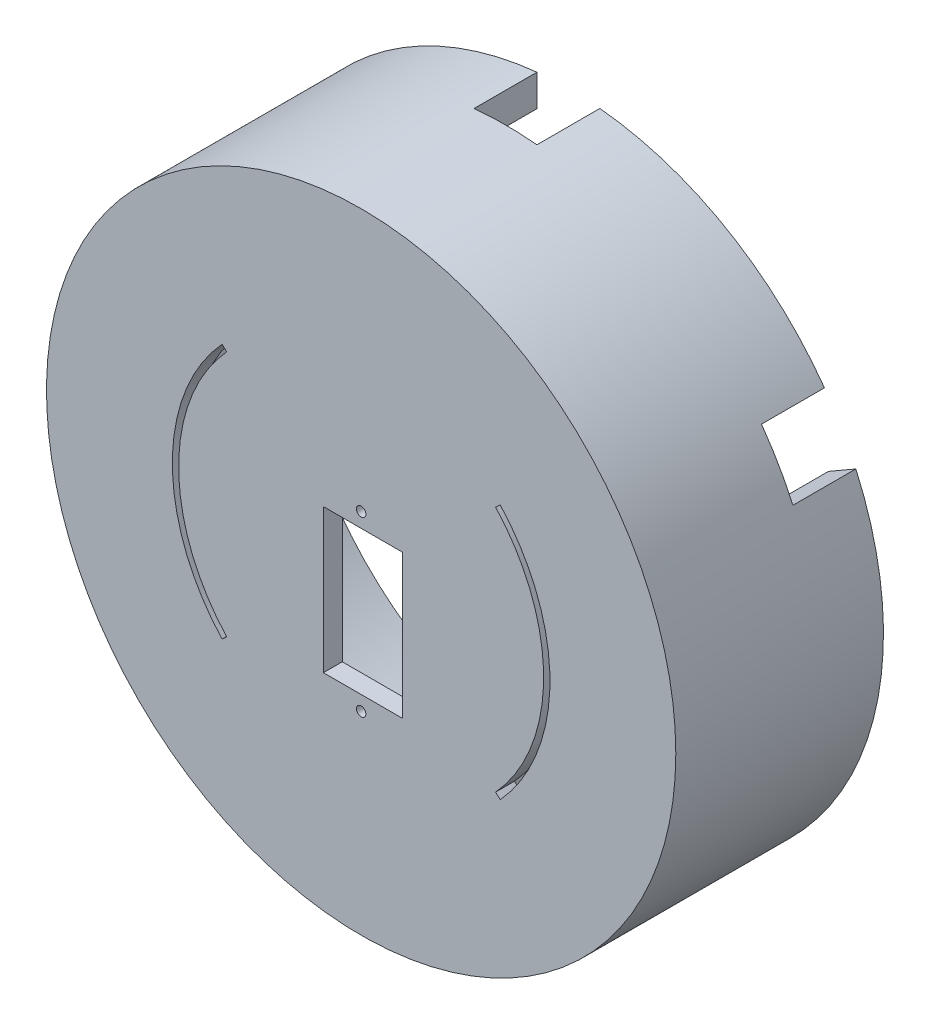
SolidWorks part; units mm, degrees
ref_plane "Front Plane" through (0, 0, 0) normal (0, 0, 1) x (1, 0, 0)
ref_plane "Top Plane" through (0, 0, 0) normal (0, 1, 0) x (1, 0, 0)
ref_plane "Right Plane" through (0, 0, 0) normal (1, 0, 0) x (0, 0, -1)
sketch "Sketch1" plane through (0, 0, 0) normal (0, 0, 1) x (1, 0, 0)
  line L0 (-5.1956, 27.9914) -> (49994.8044, 27.9914) construction
  line L1 (-6, -2.32) -> (6.6, -2.32) construction
  line L2 (-5.002, -4.6686) -> (49994.998, -4.6686) construction
  line L3 (-5.7, 27.9914) -> (6.9, 27.9914)
  line L4 (6.9, 10.7264) -> (6.9, 50010.7264) construction
  line L5 (-6, 16.86) -> (6.6, 16.86) construction
  line L6 (-5.7, 12.1783) -> (-5.7, 50012.1783) construction
  line L7 (-5.7, 22.86) -> (6.9, 22.86)
  line L8 (-5.7, 0) -> (6.9, 0)
  line L11 (-5.7, -4.6686) -> (6.9, -4.6686)
  line L13 (0.6, -4.6686) -> (0.6, 28.06) construction
  line L16 (-6, 25.18) -> (6.6, 25.18) construction
  line L19 (0.6, 28.06) -> (0.6, 22.86) construction
  line L20 (-5.7, 27.9914) -> (-5.7, 22.86)
  line L21 (-5.7, 0) -> (6.9, 0)
  line L22 (-5.7, 0) -> (-5.7, -4.6686)
  line L23 (-5.7, -4.6686) -> (6.9, -4.6686)
  line L24 (6.9, 0) -> (6.9, -4.6686)
  line L25 (0.6, -4.6686) -> (0.6, 0) construction
  line L26 (-5.7, -2.3343) -> (6.9, -2.3343) construction
  line L27 (6.9, 27.9914) -> (6.9, 22.86)
  line L29 (-5.7, 22.86) -> (6.9, 22.86)
  line L30 (-5.7, 22.86) -> (-5.7, 0)
  line L31 (-5.7, 0) -> (6.9, 0)
  line L32 (6.9, 22.86) -> (6.9, 0)
  line L33 (0.6, 0) -> (0.6, 22.86) construction
  line L34 (-5.7, 11.43) -> (6.9, 11.43) construction
  circle A3 centre (0.3, 25.18) radius 1.28
  circle A4 centre (0.3, -2.32) radius 1.28
  circle A5 centre (0.3, 16.86) radius 50
  point P287 (0.6, -2.3343)
  point P359 (0.6, 25.46)
  point P550 (0.6, 11.73)
  point P577 (0.6, 11.43)
  dimension "D3" = 100
  dimension "D4" = 2.56
  dimension "D5" = 2.56
  dimension "D1" = 12.6
  dimension "D2" = 32.66
extrude "Boss-Extrude2" add sketch "Sketch1" along normal blind 3 contours A5
sketch "Sketch2" plane through (0, 0, 0) normal (0, 0, -1) x (-1, 0, 0)
  line L1 (5.7, 0) -> (-6.9, 0)
  line L2 (5.7, 0) -> (5.7, 22.86)
  line L3 (5.7, 22.86) -> (-6.9, 22.86)
  line L4 (-6.9, 0) -> (-6.9, 22.86)
  line L5 (-0.6, 22.86) -> (-0.6, 0) construction
  line L6 (5.7, 11.43) -> (-6.9, 11.43) construction
  circle A0 centre (-0.3, -2.32) radius 0.75
  circle A1 centre (-0.3, 25.18) radius 0.75
  point P364 (-0.6, 11.43)
  dimension "D1" = 1.5
  dimension "D2" = 1.5
sketch "Sketch4" plane through (0, 0, 0) normal (0, 0, -1) x (-1, 0, 0)
  circle A0 centre (-0.3, 16.86) radius 50
  circle A1 centre (-0.3, 16.86) radius 45
  dimension "D1" = 5
  dimension "D2" = 100
extrude "Boss-Extrude3" add sketch "Sketch4" along normal blind 30
sketch "Sketch6" plane through (0, 0, -30) normal (0, 0, -1) x (-1, 0, 0)
  line L0 (-0.2348, -8.2498) -> (-0.2348, -50008.2498) construction
  line L10 (-44.9272, 48.3238) -> (-32.8296, 41.3393)
  line L11 (-5.2348, -37.5202) -> (4.7652, -37.5202)
  line L19 (-5.2348, -37.5202) -> (-5.2348, -23.5511)
  line L24 (-5.2348, -23.5511) -> (4.7652, -23.5511)
  line L25 (4.7652, -37.5202) -> (4.7652, -23.5511)
  line L30 (-5.2348, -37.5202) -> (4.7652, -23.5511) construction
  line L31 (-5.2348, -23.5511) -> (4.7652, -37.5202) construction
  line L32 (-44.9272, 48.3238) -> (-49.9272, 39.6635)
  line L33 (-49.9272, 39.6635) -> (-37.8296, 32.679)
  line L34 (-32.8296, 41.3393) -> (-37.8296, 32.679)
  line L35 (49.262, 39.7764) -> (37.1645, 32.7919)
  line L36 (49.262, 39.7764) -> (44.262, 48.4366)
  line L37 (44.262, 48.4366) -> (32.1645, 41.4521)
  line L38 (37.1645, 32.7919) -> (32.1645, 41.4521)
  line L40 (-5.2348, 56.0498) -> (4.7652, 56.0498)
  line L41 (-5.2348, 56.0498) -> (-5.2348, 72.8757)
  line L42 (-5.2348, 72.8757) -> (4.7652, 72.8757)
  line L43 (4.7652, 56.0498) -> (4.7652, 72.8757)
  line L44 (-5.2348, 56.0498) -> (4.7652, 72.8757) construction
  line L45 (-5.2348, 72.8757) -> (4.7652, 56.0498) construction
  circle A0 centre (-0.3, 16.86) radius 45 construction
  point P0 (-0.2348, -30.5356)
  point P8 (-0.2348, 64.4627)
  point P18 (-0.3, 16.86)
  dimension "D1" = 10
  dimension "D3" = 10
  dimension "D2" = 3
extrude "Cut-Extrude5" cut sketch "Sketch6" against normal blind 10
extrude "Cut-Extrude6" cut sketch "Sketch2" against normal through all
sketch "Sketch7" plane through (0, 0, 3) normal (0, 0, 1) x (1, 0, 0)
  line L0 (0.3, 66.86) -> (0.3, -33.14) construction
  line L1 (-21.8024, 37.1451) -> (-21.0656, 36.4689)
  line L2 (-21.8024, -3.4251) -> (-21.0656, -2.7489)
  line L3 (21.6656, -2.7489) -> (22.4024, -3.4251)
  line L4 (21.6656, 36.4689) -> (22.4024, 37.1451)
  circle A0 centre (0.3, 16.86) radius 50 construction
  arc A1 (-21.8024, 37.1451) -> (-21.8024, -3.4251) centre (0.3, 16.86) ccw
  arc A2 (-21.0656, 36.4689) -> (-21.0656, -2.7489) centre (0.3, 16.86) ccw
  arc A3 (21.6656, -2.7489) -> (21.6656, 36.4689) centre (0.3, 16.86) ccw
  arc A4 (22.4024, -3.4251) -> (22.4024, 37.1451) centre (0.3, 16.86) ccw
  dimension "D1" = 1
  dimension "D2" = 60
extrude "Cut-Extrude7" cut sketch "Sketch7" against normal blind 10
